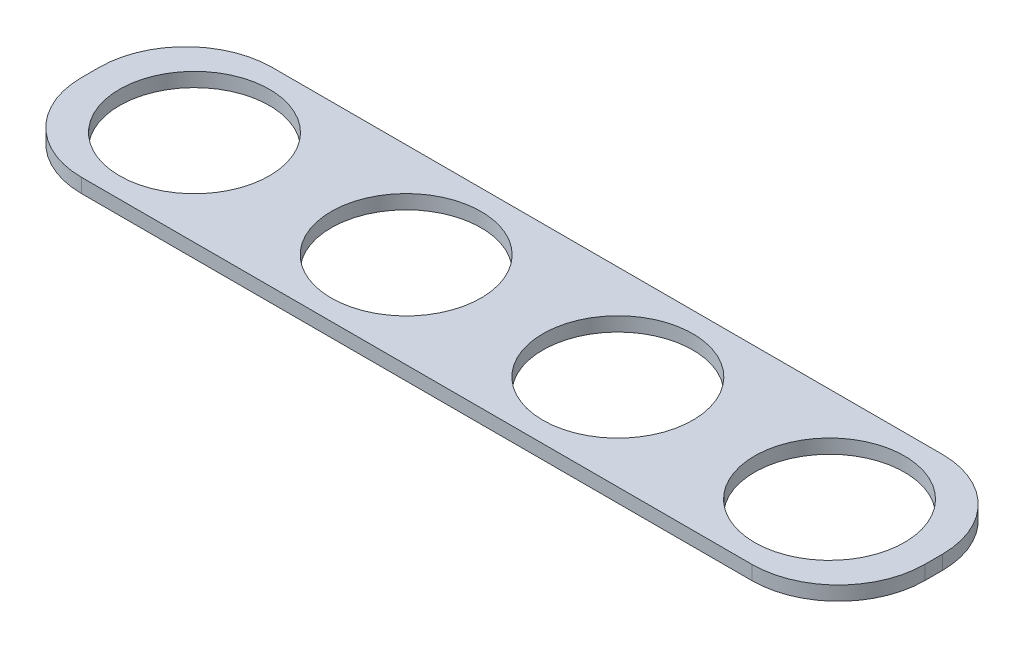
SolidWorks part; units mm, degrees
ref_plane "Front Plane" through (0, 0, 0) normal (0, 0, 1) x (1, 0, 0)
ref_plane "Top Plane" through (0, 0, 0) normal (0, 1, 0) x (1, 0, 0)
ref_plane "Right Plane" through (0, 0, 0) normal (1, 0, 0) x (0, 0, -1)
sketch "Sketch1" plane through (0, 0, 0) normal (0, 1, 0) x (1, 0, 0)
  line L1 (23.9, -5.4) -> (-23.9, -5.4)
  line L2 (23.9, -5.4) -> (23.9, 5.4)
  line L3 (23.9, 5.4) -> (-23.9, 5.4)
  line L4 (-23.9, -5.4) -> (-23.9, 5.4)
  line L5 (23.9, -5.4) -> (-23.9, 5.4) construction
  line L6 (23.9, 5.4) -> (-23.9, -5.4) construction
  point P0 (0, 0)
  dimension "D1" = 47.8
  dimension "D2" = 10.8
extrude "Boss-Extrude1" add sketch "Sketch1" along normal blind 0.8
sketch "Sketch2" plane through (0, 0.8, 0) normal (0, 1, 0) x (1, 0, 0)
  line L0 (0, 5.4) -> (0, -5.4) construction
  line L5 (23.9, 5.4) -> (-23.9, 5.4) construction
  line L6 (-23.9, -5.4) -> (23.9, -5.4) construction
  line L7 (18, 0) -> (6, 0) construction
  line L8 (-18, 0) -> (-6, 0) construction
  line L9 (6, 0) -> (-6, 0) construction
  circle A4 centre (-18, 0) radius 4.25
  circle A5 centre (18, 0) radius 4.25
  circle A6 centre (-6, 0) radius 4.25
  circle A7 centre (6, 0) radius 4.25
  point P12 (0, 0)
  dimension "D2" = 12
  dimension "D1" = 8.5
extrude "Cut-Extrude1" cut sketch "Sketch2" against normal up to next
fillet "Fillet1" radius 4.9 4 edges at (-23.9, 0.4, -5.4) (23.9, 0.4, -5.4) (23.9, 0.4, 5.4) (-23.9, 0.4, 5.4)
